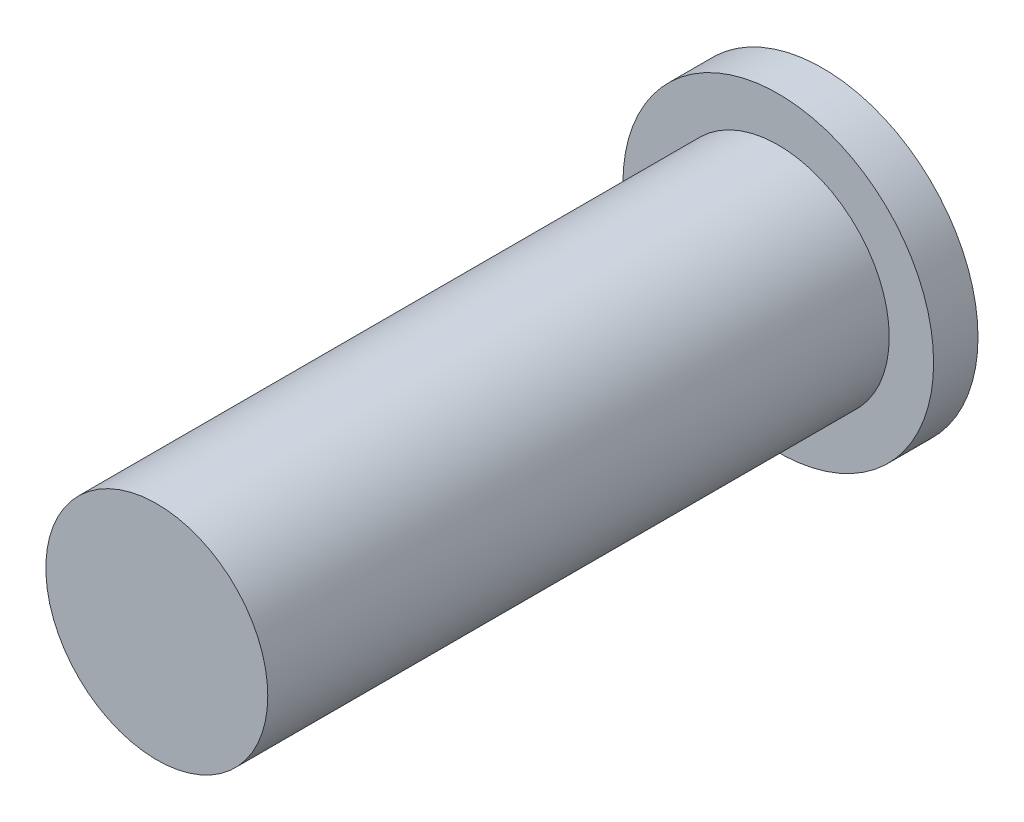
SolidWorks part; units mm, degrees
ref_plane "Piano frontale" through (0, 0, 0) normal (0, 0, 1) x (1, 0, 0)
ref_plane "Piano superiore" through (0, 0, 0) normal (0, 1, 0) x (1, 0, 0)
ref_plane "Piano destro" through (0, 0, 0) normal (1, 0, 0) x (0, 0, -1)
sketch "Schizzo2" plane through (0, 0, 0) normal (1, 0, 0) x (0, 0, -1)
  line L0 (0, 2.5) -> (0, 0)
  line L5 (0, 2.5) -> (14, 2.5)
  line L6 (0, 0) -> (19.0571, 0) construction
  line L7 (14, 2.5) -> (14, 3.5)
  line L8 (15, 2.5) -> (15, 0)
  line L9 (0, 0) -> (15, 0)
  line L10 (14, 3.5) -> (15, 3.5)
  line L11 (15, 3.5) -> (15, 2.5)
  dimension "D1" = 15
  dimension "D6" = 2.5
  dimension "D7" = 1
  dimension "D8" = 1
revolve "Rivoluzione1" add sketch "Schizzo2" angle 360 about L6
